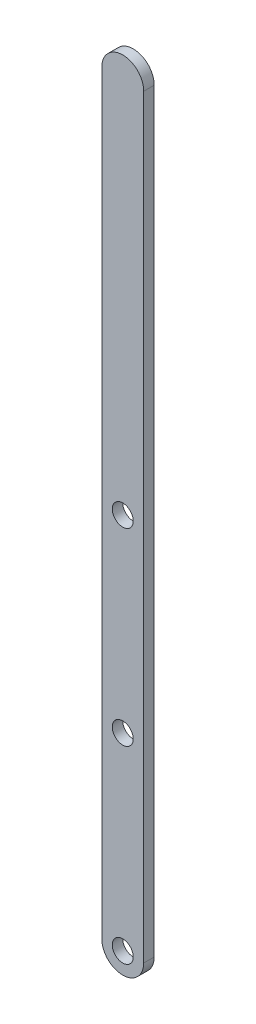
SolidWorks part; units mm, degrees
material "5052-H32"
ref_plane "Front Plane" through (0, 0, 0) normal (0, 0, 1) x (1, 0, 0)
ref_plane "Top Plane" through (0, 0, 0) normal (0, 1, 0) x (1, 0, 0)
ref_plane "Right Plane" through (0, 0, 0) normal (1, 0, 0) x (0, 0, -1)
sketch "Sketch1" plane through (0, 0, 0) normal (0, 0, 1) x (1, 0, 0)
  line L0 (-25.4, -457.2) -> (-25.4, 0)
  line L1 (25.4, 0) -> (25.4, -457.2)
  line L2 (25.4, 0) -> (25.4, 457.2)
  line L3 (0, 0) -> (0, -228.6) construction
  line L4 (-25.4, 0) -> (-25.4, 457.2)
  arc A0 (25.4, 0) -> (-25.4, 0) centre (0, 0) ccw construction
  arc A1 (-25.4, -457.2) -> (25.4, -457.2) centre (0, -457.2) ccw
  circle A2 centre (0, 0) radius 12.7
  circle A3 centre (0, -457.2) radius 12.7
  circle A5 centre (0, -228.6) radius 12.7
  arc A6 (25.4, 457.2) -> (-25.4, 457.2) centre (0, 457.2) ccw
  dimension "D1" = 25.4
  dimension "D3" = 25.4
  dimension "D4" = 25.4
  dimension "D5" = 228.6
  dimension "D2" = 457.2
  dimension "D6" = 457.2
extrude "Boss-Extrude1" add sketch "Sketch1" along normal blind 12.7
sketch "Sketch2" plane through (0, 0, 12.7) normal (0, 0, 1) x (1, 0, 0)
  line L0 (0, -457.2) -> (0, -381) construction
  line L1 (0, -381) -> (0, -304.8) construction
  line L2 (0, -304.8) -> (0, -228.6) construction
  line L3 (0, -228.6) -> (0, -152.4) construction
  line L4 (0, -152.4) -> (0, -76.2) construction
  line L5 (0, -457.2) -> (-263.9645, -609.6) construction
  line L6 (0, -381) -> (-276.2426, -509.814) construction
  line L7 (0, -304.8) -> (-286.4183, -409.0477) construction
  line L8 (0, -228.6) -> (-294.4142, -307.488) construction
  line L9 (0, -152.4) -> (-300.1694, -205.328) construction
  line L10 (0, -76.2) -> (-303.6401, -102.7651) construction
  line L11 (0, -76.2) -> (0, 0) construction
  line L12 (0, 0) -> (0, 76.2) construction
  line L13 (0, 76.2) -> (0, 152.4) construction
  line L14 (0, 152.4) -> (0, 228.6) construction
  line L15 (0, 228.6) -> (0, 304.8) construction
  line L16 (0, 304.8) -> (0, 381) construction
  line L17 (0, 381) -> (0, 457.2) construction
  line L18 (0, 0) -> (-304.8, 0) construction
  line L19 (0, 76.2) -> (-304.6143, 86.8374) construction
  line L20 (0, 152.4) -> (-304.0575, 173.6618) construction
  line L21 (0, 228.6) -> (-303.1303, 260.4603) construction
  line L22 (0, 304.8) -> (-301.8337, 347.22) construction
  line L23 (0, 381) -> (-300.1694, 433.928) construction
  line L24 (0, 457.2) -> (-298.1394, 520.5715) construction
  dimension "D1" = 76.2
  dimension "D2" = 304.8
  dimension "D3" = 5
  dimension "D4" = 120
  dimension "D5" = 5
  dimension "D6" = 5
  dimension "D7" = 5
  dimension "D8" = 5
  dimension "D9" = 5
  dimension "D10" = 2
  dimension "D11" = 2
  dimension "D12" = 2
  dimension "D13" = 2
  dimension "D14" = 2
  dimension "D15" = 2
